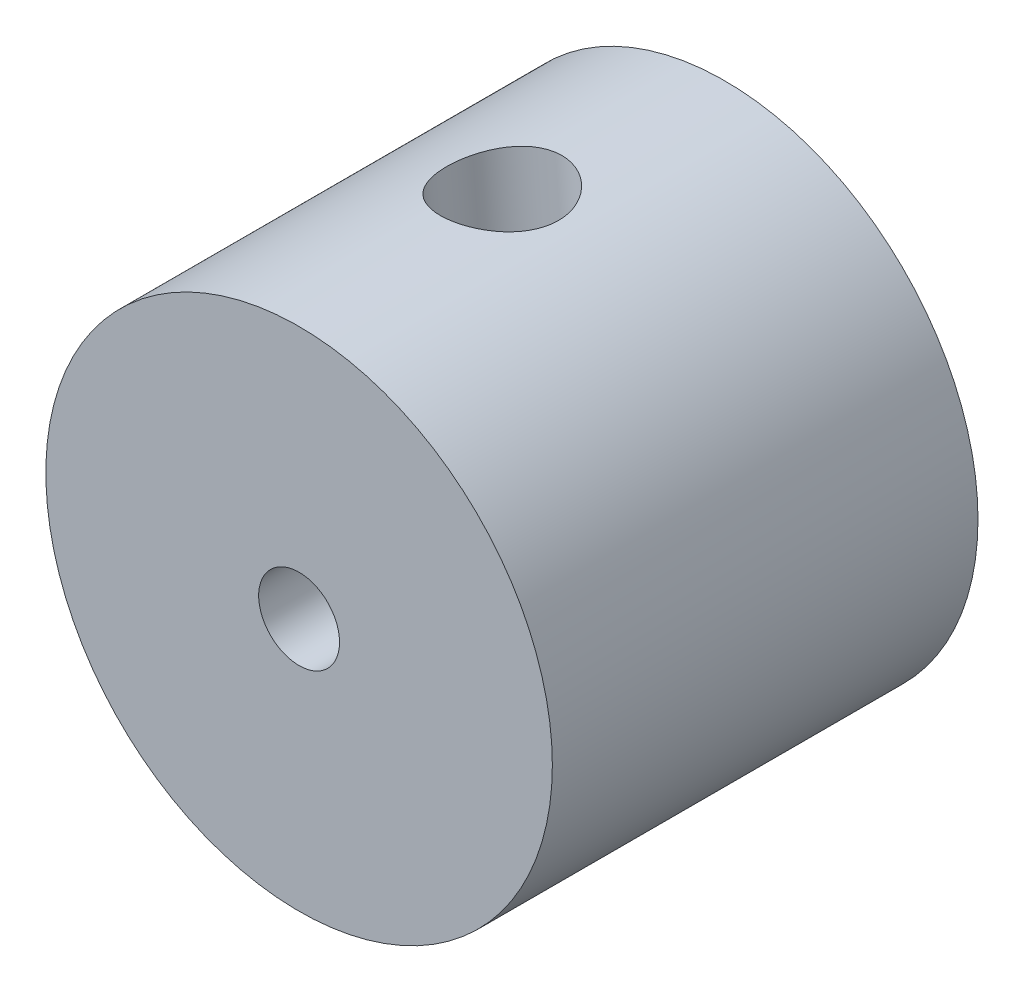
SolidWorks part; units mm, degrees
ref_plane "Front Plane" through (0, 0, 0) normal (0, 0, 1) x (1, 0, 0)
ref_plane "Top Plane" through (0, 0, 0) normal (0, 1, 0) x (1, 0, 0)
ref_plane "Right Plane" through (0, 0, 0) normal (1, 0, 0) x (0, 0, -1)
sketch "Sketch1" plane through (0, 0, 0) normal (0, 0, 1) x (1, 0, 0)
  line L0 (-102.6747, 42.083) -> (-100.7747, 42.083)
  line L1 (-95.7747, 42.083) -> (-107.6747, 42.083) construction
  circle A0 centre (-101.7247, 42.083) radius 5.95
  circle A1 centre (-101.7247, 42.083) radius 0.95
extrude "Boss-Extrude2" add sketch "Sketch1" along normal blind 10 contours A0
sketch "Sketch12" plane through (0, 0, 10) normal (0, 0, 1) x (1, 0, 0)
  line L0 (-107.6747, 42.083) -> (-95.7747, 42.083) construction
  line L1 (-102.6747, 42.083) -> (-100.7747, 42.083)
  circle A0 centre (-101.7247, 42.083) radius 5.95 construction
  circle A1 centre (-101.7247, 42.083) radius 0.95
extrude "Cut-Extrude3" cut sketch "Sketch12" against normal blind 10 contours A1
hole_wizard "#37 (0.104) Diameter Hole1" positions "3DSketch1" profile "Sketch15" hole size "#37" standard "ANSI Inch" end condition through all
sketch3d "3DSketch1"
  point P0 (-101.2289, 36.1537, 4.7368)
sketch "Sketch15" plane through (-101.2289, 36.1537, 4.7368) normal (0, 0, 1) x (0.9965, 0.0833, 0)
  line L0 (0, 0) -> (0, 12.3751)
  line L1 (0, 12.3751) -> (1.3208, 12.3751)
  line L2 (1.3208, 12.3751) -> (1.3208, 0)
  line L5 (1.3208, 0) -> (0, 0)
  line L11 (0, -6.35) -> (0, 107.95) construction
  dimension "Thru Hole Dia." = 2.6416
  dimension "Thru Hole Depth" = 12.3751
sketch "Sketch16" plane through (0, 0, 10) normal (0, 0, 1) x (1, 0, 0)
  point P0 (-101.7247, 42.083)
